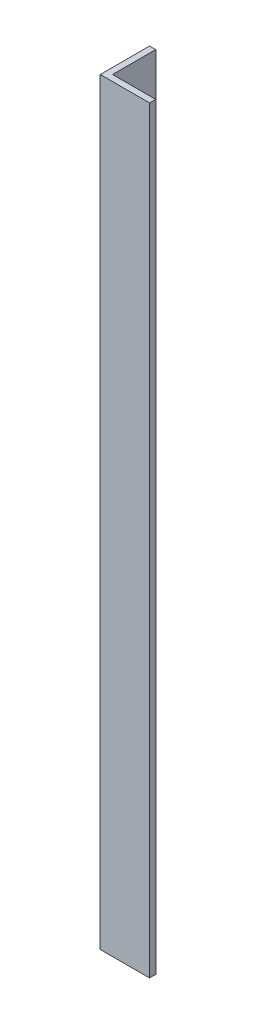
SolidWorks part; units mm, degrees
ref_plane "Alzado" through (0, 0, 0) normal (0, 0, 1) x (1, 0, 0)
ref_plane "Planta" through (0, 0, 0) normal (0, 1, 0) x (1, 0, 0)
ref_plane "Vista lateral" through (0, 0, 0) normal (1, 0, 0) x (0, 0, -1)
sketch "Croquis1" plane through (0, 0, 0) normal (0, 1, 0) x (1, 0, 0)
  line L0 (0, 0) -> (0, 76.2)
  line L1 (0, 0) -> (76.2, 0)
  line L2 (9.525, 9.525) -> (76.2, 9.525)
  line L3 (9.525, 9.525) -> (9.525, 76.2)
  line L4 (0, 76.2) -> (9.525, 76.2)
  line L5 (76.2, 9.525) -> (76.2, 0)
  line L6 (76.2, 0) -> (76.2612, 0.1521)
  dimension "D1" = 76.2
  dimension "D2" = 76.2
  dimension "D3" = 9.525
extrude "Saliente-Extruir1" add sketch "Croquis1" along normal blind 1170.475 contours L5 L2 L3 L4 L0 L1
